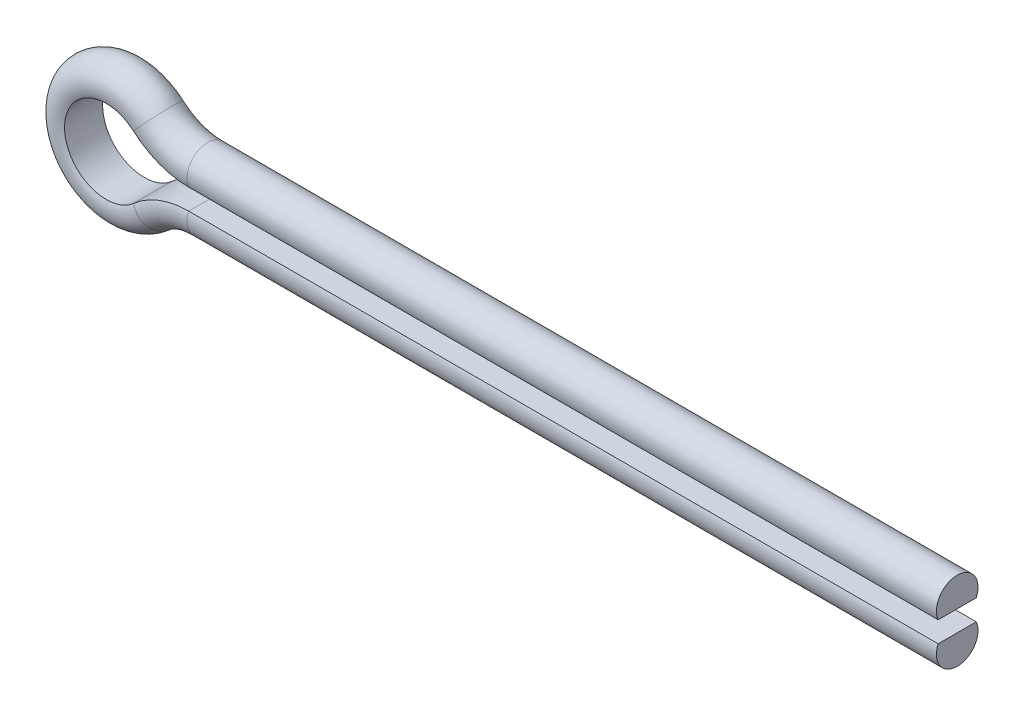
SolidWorks part; units mm, degrees
ref_plane "Front Plane" through (0, 0, 0) normal (0, 0, 1) x (1, 0, 0)
ref_plane "Top Plane" through (0, 0, 0) normal (0, 1, 0) x (1, 0, 0)
ref_plane "Right Plane" through (0, 0, 0) normal (1, 0, 0) x (0, 0, -1)
sketch "Sketch1" plane through (0, 0, 0) normal (0, 0, 1) x (1, 0, 0)
  line L0 (0, 0) -> (38.543, 0) construction
  line L1 (9.9216, 1.25) -> (100, 1.25)
  line L2 (9.9216, -1.25) -> (100, -1.25)
  arc A0 (3.3072, 3.75) -> (3.3072, -3.75) centre (0, 0) ccw
  arc A1 (9.9216, -1.25) -> (3.3072, -3.75) centre (9.9216, -11.25) ccw
  arc A2 (9.9216, 1.25) -> (3.3072, 3.75) centre (9.9216, 11.25) cw
  point P9 (4.8412, -1.25)
  point P12 (4.8412, 1.25)
  dimension "D1" = 10
  dimension "D4" = 10
  dimension "D2" = 2.5
  dimension "D3" = 100
ref_plane "Plane1" through (100, 1.25, 0) normal (1, 0, 0) x (0, 0, -1)
sketch "Sketch2" plane through (100, 1.25, 0) normal (1, 0, 0) x (0, 0, -1)
  line L0 (-2.2913, 0) -> (2.2913, 0)
  line L2 (0, 3.75) -> (0, -6.25) construction
  arc A0 (2.2913, 0) -> (-2.2913, 0) centre (0, 1) ccw
  dimension "D1" = 5
sweep "Sweep1" add profiles "Sketch2" path "Sketch1"
